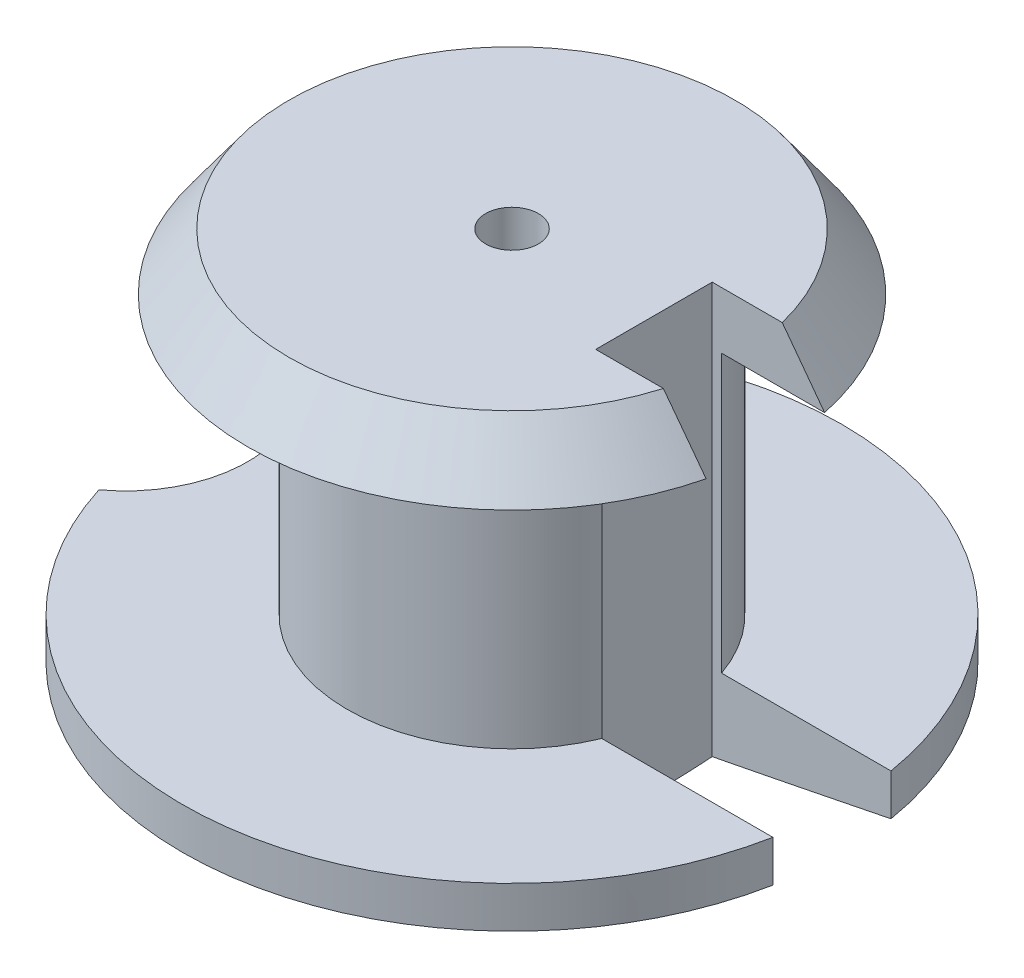
SolidWorks part; units mm, degrees
ref_plane "Plan de face" through (0, 0, 0) normal (0, 0, 1) x (1, 0, 0)
ref_plane "Plan de dessus" through (0, 0, 0) normal (0, 1, 0) x (1, 0, 0)
ref_plane "Plan de droite" through (0, 0, 0) normal (1, 0, 0) x (0, 0, -1)
sketch "Esquisse1" plane through (0, 0, 0) normal (0, 0, 1) x (1, 0, 0)
  line L0 (0, 71.5214) -> (0, -68.1214) construction
  line L1 (-45.723, 74.1929) -> (-5.4087, 74.1929)
  line L2 (-5.4087, 74.1929) -> (-5.4087, 60.5929)
  line L3 (-5.4087, 60.5929) -> (0, 60.5929)
  line L4 (0, 60.5929) -> (0, -16.6357)
  line L5 (0, -16.6357) -> (-67.5801, -2.7929)
  line L6 (-67.5801, -2.7929) -> (-67.5801, 5.7071)
  line L7 (-67.5801, 5.7071) -> (-33.7901, 5.7071)
  line L8 (-33.7901, 5.7071) -> (-33.7901, 62.5357)
  line L9 (-33.7901, 62.5357) -> (-54.1985, 62.5357)
  line L10 (-54.1985, 62.5357) -> (-45.723, 74.1929)
revolve "Révolution1" add sketch "Esquisse1" angle 360 about L4
sketch "Esquisse2" plane through (0, 74.1929, 0) normal (0, 1, 0) x (1, 0, 0)
  line L1 (30.0072, 11.0505) -> (74.2093, 11.0505)
  line L2 (30.0072, 11.0505) -> (30.0072, -12.8474)
  line L3 (30.0072, -12.8474) -> (74.2093, -12.8474)
  line L4 (74.2093, 11.0505) -> (74.2093, -12.8474)
  circle A0 centre (-79.2405, 0) radius 25.042
extrude "Enlèv. mat.-Extru.1" cut sketch "Esquisse2" against normal blind 90
